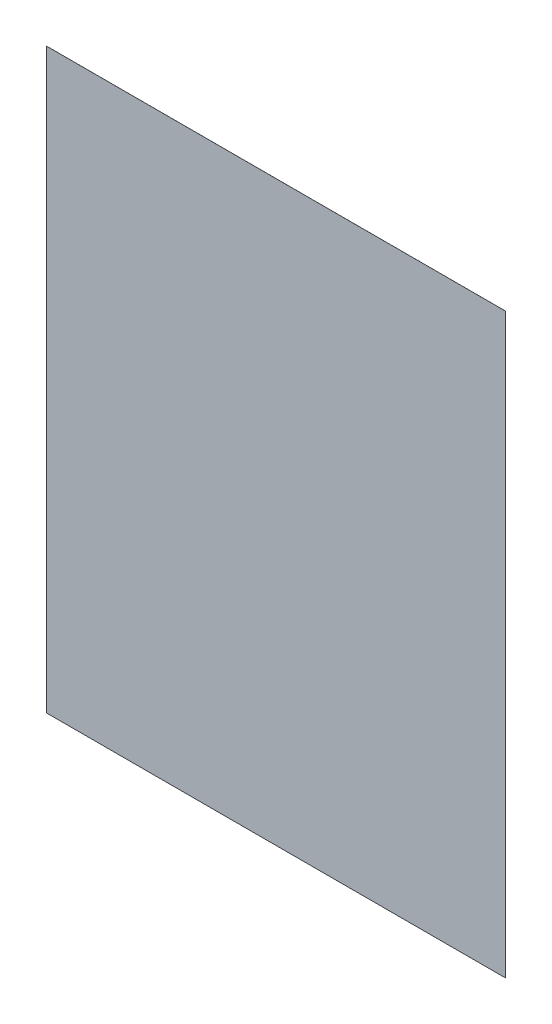
SolidWorks part; units mm, degrees
ref_plane "前视基准面" through (0, 0, 0) normal (0, 0, 1) x (1, 0, 0)
ref_plane "上视基准面" through (0, 0, 0) normal (0, 1, 0) x (1, 0, 0)
ref_plane "右视基准面" through (0, 0, 0) normal (1, 0, 0) x (0, 0, -1)
sketch "草图1" plane through (0, 0, 0) normal (0, 0, 1) x (1, 0, 0)
  line L0 (-1.7526, -2.1016) -> (1.5889, -2.1016)
  line L1 (1.5889, -2.1016) -> (1.5889, 2.1016)
  line L2 (1.5889, 2.1016) -> (-1.7526, 2.1016)
  line L3 (-1.7526, 2.1016) -> (-1.7526, -2.1016)
extrude "凸台-拉伸1" add sketch "草图1" along normal blind 0.0003 from offset 0
